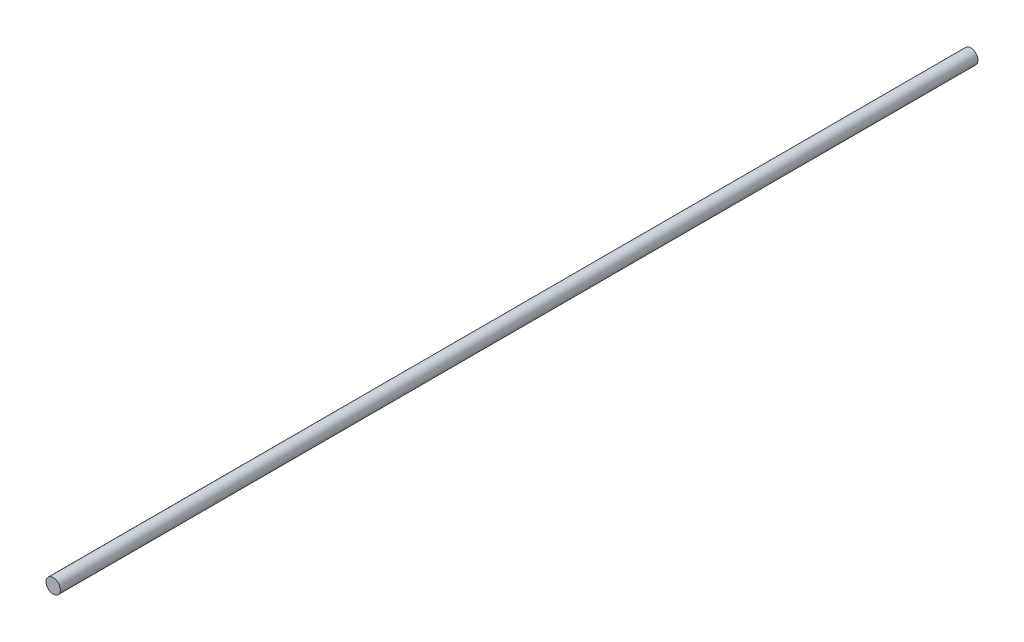
SolidWorks part; units mm, degrees
ref_plane "前视基准面" through (0, 0, 0) normal (0, 0, 1) x (1, 0, 0)
ref_plane "上视基准面" through (0, 0, 0) normal (0, 1, 0) x (1, 0, 0)
ref_plane "右视基准面" through (0, 0, 0) normal (1, 0, 0) x (0, 0, -1)
sketch "草图1" plane through (0, 0, 0) normal (0, 0, 1) x (1, 0, 0)
  circle A0 centre (-14.8143, 7.8929) radius 4
extrude "凸台-拉伸1" add sketch "草图1" along normal blind 511.42
